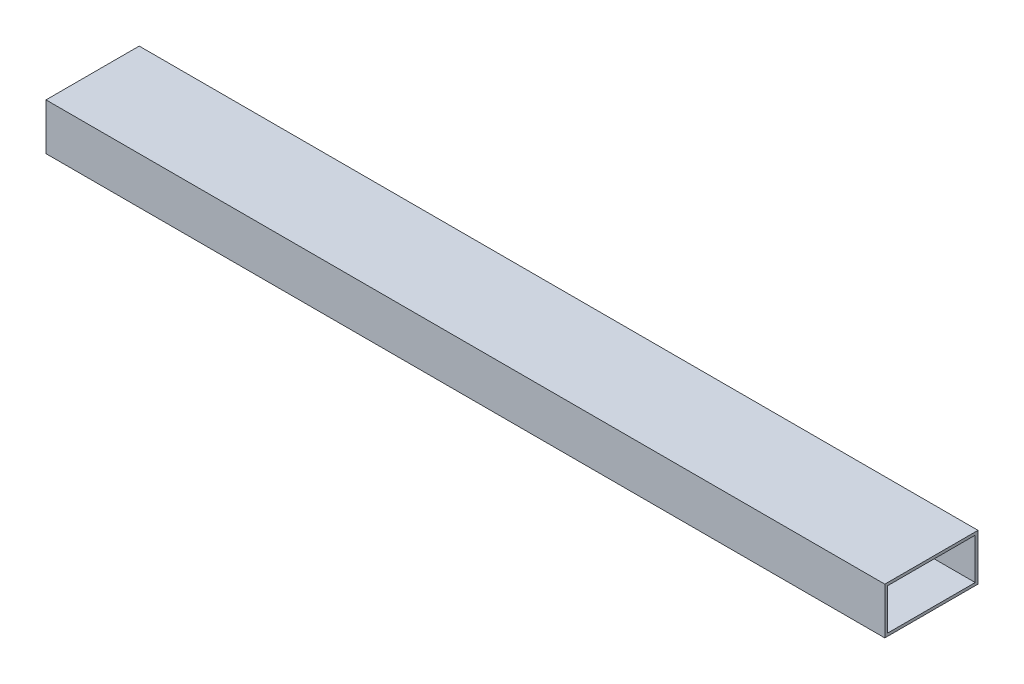
SolidWorks part; units mm, degrees
ref_plane "Front Plane" through (0, 0, 0) normal (0, 0, 1) x (1, 0, 0)
ref_plane "Top Plane" through (0, 0, 0) normal (0, 1, 0) x (1, 0, 0)
ref_plane "Right Plane" through (0, 0, 0) normal (1, 0, 0) x (0, 0, -1)
sketch "Sketch2" plane through (0, 0, 0) normal (1, 0, 0) x (0, 0, -1)
  line L1 (0, 0) -> (-50.8, 0)
  line L2 (0, 0) -> (0, 25.4)
  line L3 (0, 25.4) -> (-50.8, 25.4)
  line L4 (-50.8, 0) -> (-50.8, 25.4)
  dimension "D1" = 50.8
  dimension "D2" = 25.4
extrude "Extrude-Thin1" add sketch "Sketch2" along normal blind 457.2 thin
